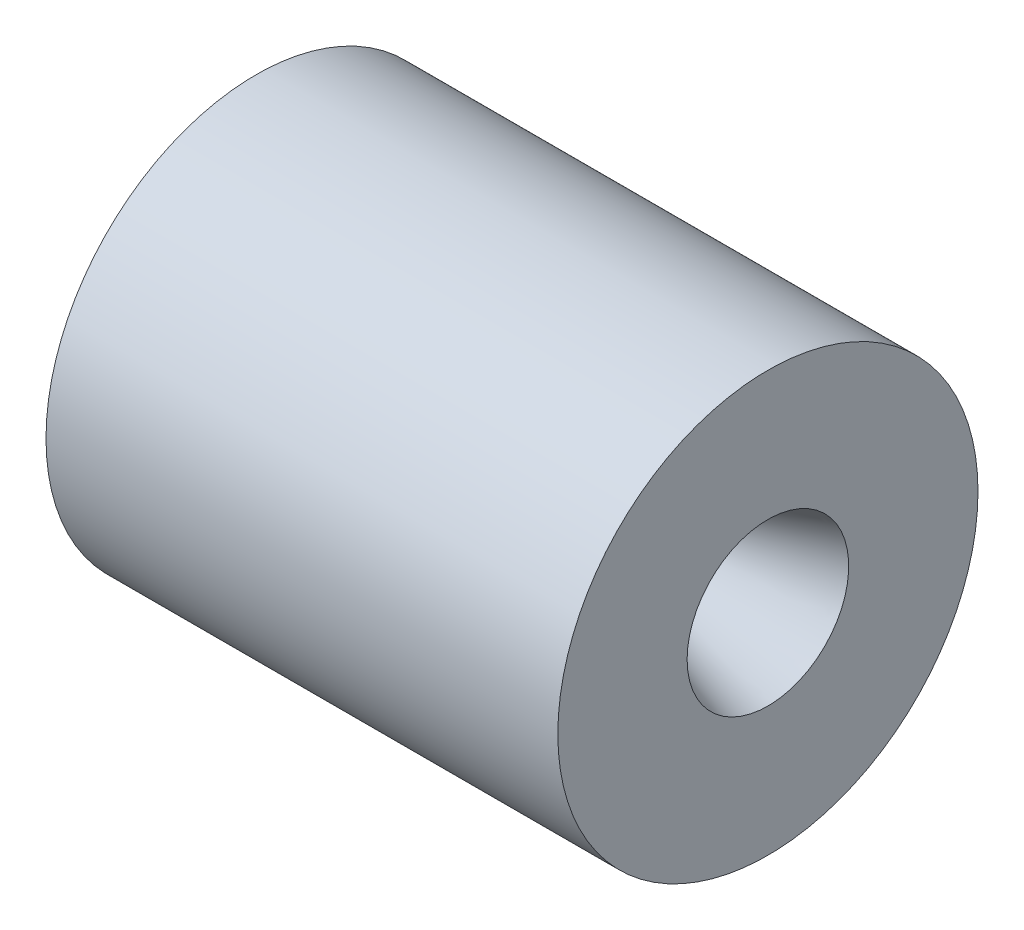
SolidWorks part; units mm, degrees
ref_plane "Front Plane" through (0, 0, 0) normal (0, 0, 1) x (1, 0, 0)
ref_plane "Top Plane" through (0, 0, 0) normal (0, 1, 0) x (1, 0, 0)
ref_plane "Right Plane" through (0, 0, 0) normal (1, 0, 0) x (0, 0, -1)
sketch "Model" plane through (0, 0, 0) normal (0, 0, 1) x (1, 0, 0)
  line L0 (0, 55.1403) -> (23.151, 55.1403)
  line L1 (95.1514, 35.8478) -> (128.5669, 16.5553)
  line L2 (0, 0) -> (185.6492, 0) construction
  line L3 (0, 55.1403) -> (0, 76.2003)
  line L4 (0, 76.2003) -> (185.6492, 76.2003)
  line L5 (185.6492, 76.2003) -> (185.6492, 29.3103)
  arc A0 (95.1514, 35.8478) -> (23.151, 55.1403) centre (23.151, -88.8606) ccw
  arc A1 (128.5669, 16.5553) -> (138.9057, 13.7851) centre (138.9057, 34.4627) ccw
  arc A2 (138.9057, 13.7851) -> (140.6089, 14.0681) centre (138.9057, 19.051) ccw
  spline S0 degree 2 poles (140.6089, 14.0681) (181.4601, 28.0309) (185.6492, 29.3103) knots 0 0 0 1 1 1
  dimension "D1" = 55.1403
  dimension "D2" = 21.06
revolve "Revolve1" add sketch "Model" angle 360 about L2
hole_wizard "13/64 (0.20313) Diameter Hole1" positions "Sketch2" profile "Sketch3" hole size "13/64" standard "ANSI Inch"
sketch "Sketch2" plane through (0, 0, 0) normal (-1, 0, 0) x (0, 0, 1)
  point P0 (69, 0)
  dimension "D1" = 69
sketch "Sketch3" plane through (0, 0, 69) normal (0, 1, 0) x (0, 0, 1)
  line L0 (0, 0) -> (0, 14.2501)
  line L1 (0, 14.2501) -> (2.5798, 12.7)
  line L2 (2.5798, 12.7) -> (2.5798, 0)
  line L5 (2.5798, 0) -> (0, 0)
  line L10 (0, 14.2501) -> (-2.5798, 12.7) construction
  line L11 (0, -6.35) -> (0, 107.95) construction
  dimension "Hole Dia." = 5.1595
  dimension "Hole Depth" = 12.7
  dimension "Drill Angle" = 118
pattern_circular "CirPattern1" count 12 over 360 about axis through (0, 0, 0) along (1, 0, 0) of "13/64 (0.20313) Diameter Hole1"
